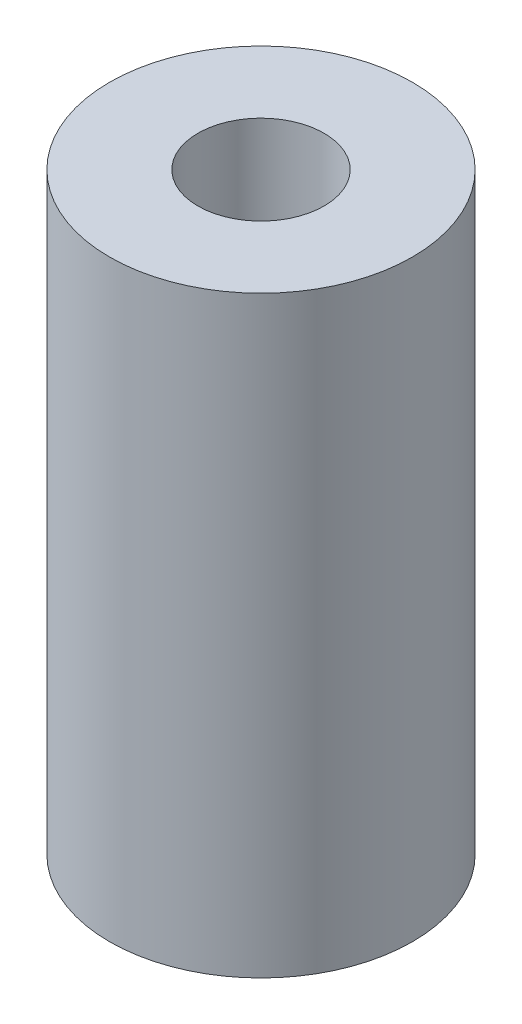
SolidWorks part; units mm, degrees
ref_plane "Front Plane" through (0, 0, 0) normal (0, 0, 1) x (1, 0, 0)
ref_plane "Top Plane" through (0, 0, 0) normal (0, 1, 0) x (1, 0, 0)
ref_plane "Right Plane" through (0, 0, 0) normal (1, 0, 0) x (0, 0, -1)
sketch "Sketch1" plane through (0, 0, 0) normal (0, 1, 0) x (1, 0, 0)
  circle A0 centre (0, 0) radius 12
  dimension "D1" = 24
extrude "Boss-Extrude1" add sketch "Sketch1" along normal blind 47
sketch "Sketch2" plane through (0, 47, 0) normal (0, 1, 0) x (1, 0, 0)
  circle A0 centre (0, 0) radius 5
  dimension "D1" = 10
extrude "Cut-Extrude1" cut sketch "Sketch2" against normal through all
